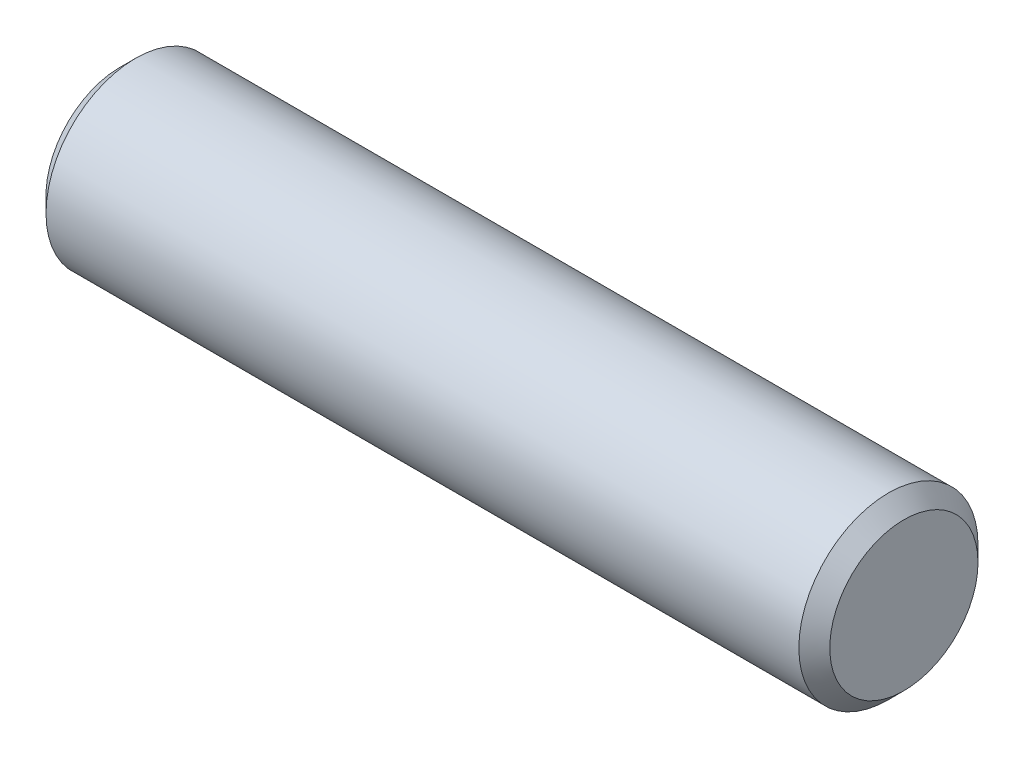
SolidWorks part; units mm, degrees
revolve "BaseBody" add sketch "BodySke" angle 360 about L14
sketch "BodySke" plane through (0, 0, 0) normal (0, 0, 1) x (1, 0, 0)
  line L0 (28.381, 15.875) -> (28.381, -6.35) construction
  line L1 (1.25, 15.875) -> (1.25, -3.175) construction
  line L2 (35, 6.35) -> (35, 3.175) construction
  line L10 (0, 4) -> (35, 4)
  line L12 (35, 4) -> (35, 0)
  line L13 (35, 0) -> (0, 0)
  line L14 (-3.175, 0) -> (107.95, 0) construction
  line L18 (0, 4) -> (0, 0)
  dimension "Diameter" = 8
  dimension "Length" = 35
  dimension "Advance" = 1.25
  dimension "Minor_dia" = 6.619
  dimension "Thread_max" = 35
cosmetic thread "ThreadCosmetic" parameters "Thread_minor"=6.619
ref_plane "Plane1" through (0, 0, 0) normal (0, 0, 1) x (1, 0, 0)
ref_plane "Plane2" through (0, 0, 0) normal (0, 1, 0) x (1, 0, 0)
ref_plane "Plane3" through (0, 0, 0) normal (1, 0, 0) x (0, 0, -1)
other "Configuration Table"
chamfer "Chamfer1" distance 0.6905 angle 45 2 edges at (35, 0, 4) (0, 0, 4)
sketch "ThdSchSke" plane through (0, 0, 0) normal (0, 0, 1) x (1, 0, 0)
  line L0 (0.4835, -3.3095) -> (0, -4)
  line L1 (0.4835, -3.3095) -> (0.967, -4)
  line L2 (0.967, -4) -> (0.967, -5)
  line L3 (-3.175, 0) -> (5.1513, 0) construction
  line L4 (0, 4) -> (0, -4) construction
  line L5 (0.967, -5) -> (0, -5)
  line L6 (0, -5) -> (0, -4)
  dimension "Thread_minor" = 6.619
  dimension "Diameter" = 8
revolve "ThreadSchematic" [suppressed] cut sketch "ThdSchSke" angle 360 about L3
pattern_linear "ThdSchPat" [suppressed]
equation "\"Thread_minor@ThreadCosmetic\" = \"Minor_dia@BodySke\""
equation "\"Chamfer@Chamfer1\" =  ( \"Diameter@BodySke\" - \"Minor_dia@BodySke\" ) / 2"
equation "\"Thread_minor@ThdSchSke\" = \"Minor_dia@BodySke\""
equation "\"Diameter@ThdSchSke\" = \"Diameter@BodySke\""
equation "\"Overcut@ThdSchSke\" = \"Diameter@BodySke\" * 1.25"
equation "\"Num_threads@ThdSchPat\" = int( (\"Thread_max@BodySke\" - \"Advance@BodySke\" ) / \"Advance@BodySke\" + 0.999 ) + 1"
equation "\"Advance@ThdSchPat\" = \"Thread_max@BodySke\" /  ( \"Num_threads@ThdSchPat\" - 1 ) 'relax it"
equation "\"Num_threads@ThdSchPat\" = \"Num_threads@ThdSchPat\" - sgn( \"Num_threads@ThdSchPat\" - 1 ) '---chamfered tips only---"
